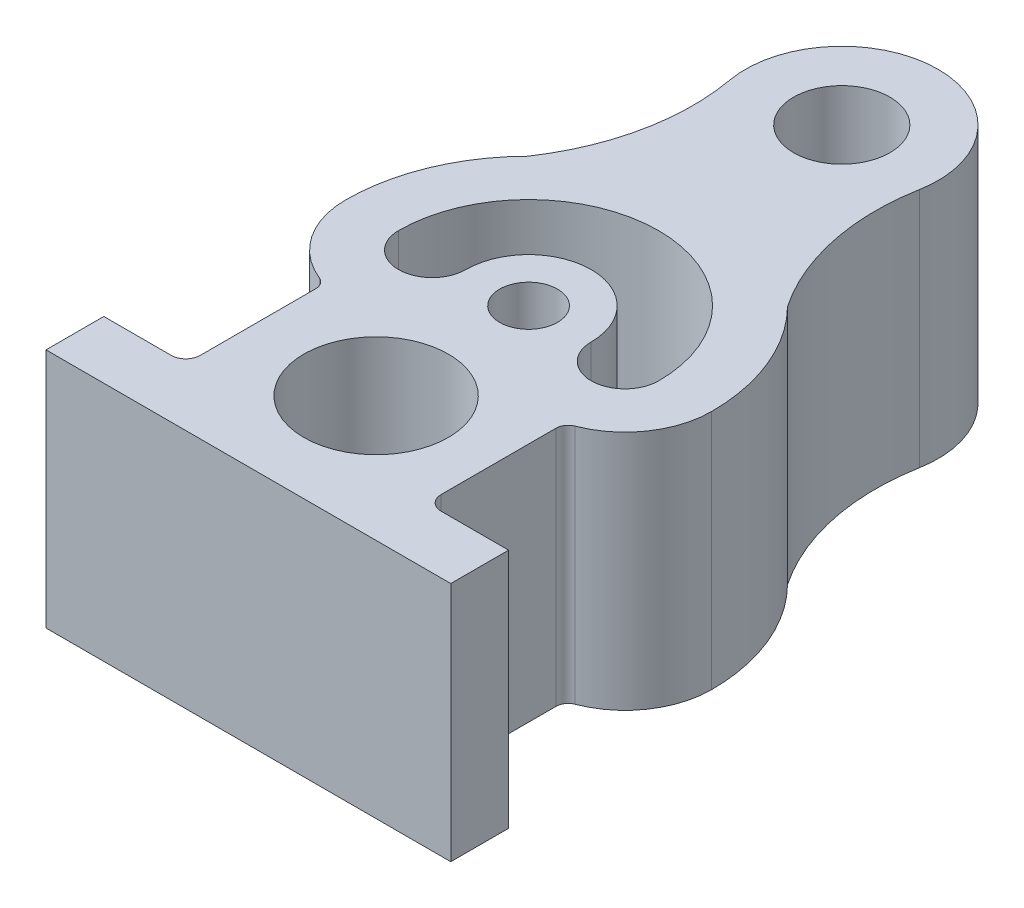
SolidWorks part; units mm, degrees
ref_plane "Front Plane" through (0, 0, 0) normal (0, 0, 1) x (1, 0, 0)
ref_plane "Top Plane" through (0, 0, 0) normal (0, 1, 0) x (1, 0, 0)
ref_plane "Right Plane" through (0, 0, 0) normal (1, 0, 0) x (0, 0, -1)
sketch "Sketch1" plane through (0, 0, 0) normal (0, 1, 0) x (1, 0, 0)
  line L0 (-84.2931, -116) -> (83.7069, -116)
  line L5 (-84.2931, -116) -> (-84.2931, -92)
  line L7 (83.7069, -92) -> (83.7069, -116)
  line L8 (-84.2931, -92) -> (-56.2931, -92)
  line L9 (83.7069, -92) -> (55.7069, -92)
  line L10 (-50.2931, -86) -> (-50.2931, -38.041)
  line L11 (49.7069, -86) -> (49.7069, -38.2715)
  arc A1 (-54, 0) -> (-26, 0) centre (-40, 0) ccw
  arc A2 (26, 0) -> (54, 0) centre (40, 0) ccw
  circle A4 centre (0.7194, -64) radius 30
  arc A5 (26, 0) -> (-26, 0) centre (0, 0) ccw
  arc A6 (54, 0) -> (-54, 0) centre (0, 0) ccw
  circle A7 centre (0, 0) radius 12
  circle A8 centre (0, 130) radius 20
  arc A9 (39.3611, 122.8795) -> (-39.3611, 122.8795) centre (0, 130) ccw
  arc A12 (52.9134, -33.6042) -> (76, 0) centre (40, 0) ccw
  arc A13 (-56.2931, -92) -> (-50.2931, -86) centre (-56.2931, -86) ccw
  arc A14 (49.7069, -86) -> (55.7069, -92) centre (55.7069, -86) ccw
  arc A15 (-76, 0) -> (-53.4281, -33.4019) centre (-40, 0) ccw
  arc A16 (-50.2931, -38.041) -> (-53.4281, -33.4019) centre (-55.2931, -38.041) ccw
  arc A17 (52.9134, -33.6042) -> (49.7069, -38.2715) centre (54.7069, -38.2715) ccw
  arc A20 (76, 0) -> (54, 53.479) centre (0, 0) ccw
  arc A21 (-39.3611, 122.8795) -> (-54, 53.479) centre (-131.8598, 106.1464) cw
  arc A22 (39.3611, 122.8795) -> (54, 53.479) centre (131.8598, 106.1464) ccw
  arc A23 (-54, 53.479) -> (-76, 0) centre (0, 0) ccw
  dimension "D1" = 130
  dimension "D2" = 6
  dimension "D3" = 6
  dimension "D4" = 5
  dimension "D5" = 5
  dimension "D6" = 80
  dimension "D7" = 40
  dimension "D11" = 14
  dimension "D12" = 24
  dimension "D13" = 26
  dimension "D14" = 54
  dimension "D15" = 36
  dimension "D16" = 76
  dimension "D17" = 60
  dimension "D23" = 94
  dimension "D24" = 94
  dimension "D8" = 168
  dimension "D9" = 24
  dimension "D10" = 24
  dimension "D19" = 40
  dimension "D20" = 100
  dimension "D21" = 34
  dimension "D22" = 34
extrude "Boss-Extrude1" add sketch "Sketch1" along normal blind 100
